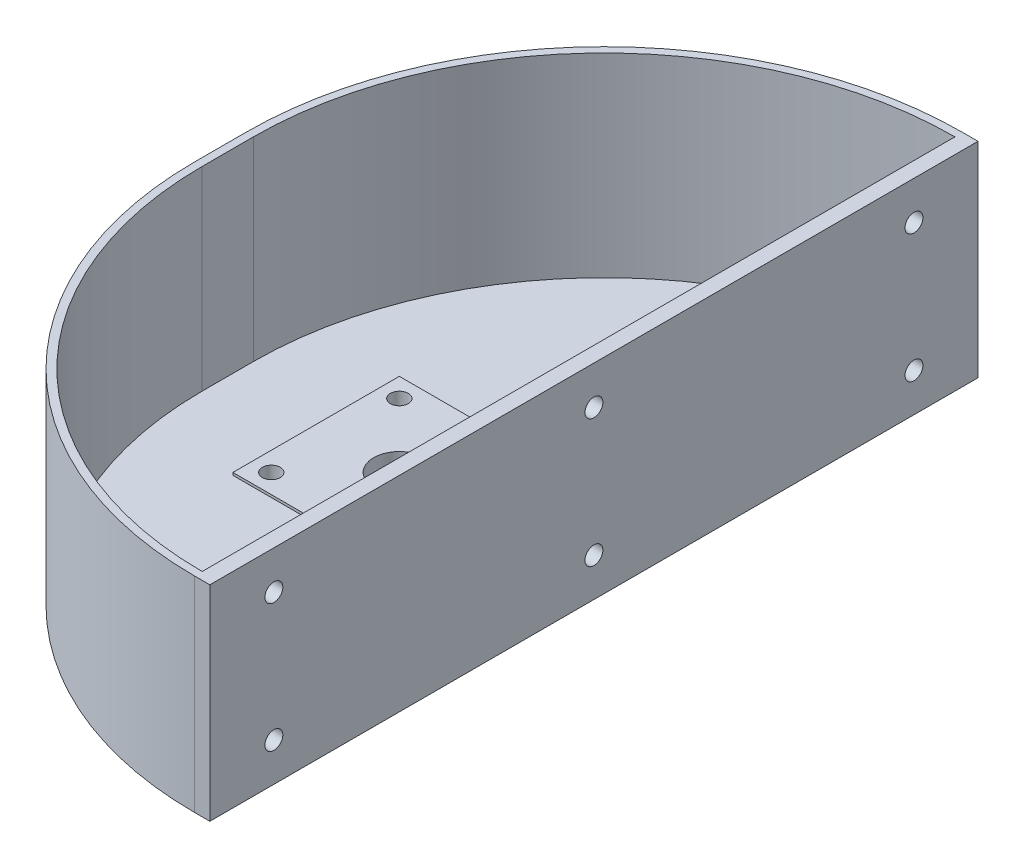
SolidWorks part; units mm, degrees
ref_plane "Спереди" through (0, 0, 0) normal (0, 0, 1) x (1, 0, 0)
ref_plane "Сверху" through (0, 0, 0) normal (0, 1, 0) x (1, 0, 0)
ref_plane "Справа" through (0, 0, 0) normal (1, 0, 0) x (0, 0, -1)
sketch "Эскиз1" plane through (0, 0, 0) normal (0, 1, 0) x (1, 0, 0)
  line L0 (0, 159.887) -> (0, 0) construction
  line L1 (0, 0) -> (281.7797, 0) construction
  line L3 (-70, -150) -> (70, -150)
  line L4 (-70, -150) -> (-70, 150)
  line L5 (-70, 150) -> (70, 150)
  line L6 (70, -150) -> (70, 150)
  line L7 (0, 150) -> (0, -150) construction
  line L8 (-70, 0) -> (70, 0) construction
  dimension "D1" = 300
  dimension "D2" = 140
extrude "Бобышка-Вытянуть1" add sketch "Эскиз1" along normal blind 4
sketch "Эскиз2" plane through (0, 0, 0) normal (0, 1, 0) x (1, 0, 0)
  line L1 (70, 150) -> (76, 150)
  line L2 (70, 150) -> (70, -150)
  line L3 (70, -150) -> (76, -150)
  line L4 (76, 150) -> (76, -150)
  dimension "D1" = 300
  dimension "D2" = 6
extrude "Бобышка-Вытянуть2" add sketch "Эскиз2" along normal blind 80
fillet "Скругление1" radius 140 2 edges at (-70, 2, -150) (-70, 2, 150)
sketch "Эскиз3" plane through (0, 4, 0) normal (0, 1, 0) x (1, 0, 0)
  line L1 (-32.5, -32.5) -> (32.5, -32.5)
  line L2 (-32.5, -32.5) -> (-32.5, 32.5)
  line L3 (-32.5, 32.5) -> (32.5, 32.5)
  line L4 (32.5, -32.5) -> (32.5, 32.5)
  line L5 (0, 32.5) -> (0, -32.5) construction
  line L6 (-32.5, 0) -> (32.5, 0) construction
  point P0 (0, 0)
  dimension "D1" = 65
extrude "Бобышка-Вытянуть3" add sketch "Эскиз3" along normal blind 1
sketch "Эскиз4" plane through (0, 5, 0) normal (0, 1, 0) x (1, 0, 0)
  line L1 (-25, -25) -> (25, -25) construction
  line L2 (-25, -25) -> (-25, 25) construction
  line L3 (-25, 25) -> (25, 25) construction
  line L4 (25, -25) -> (25, 25) construction
  line L5 (0, 25) -> (0, -25) construction
  line L6 (-25, 0) -> (25, 0) construction
  circle A0 centre (-25, 25) radius 3.5
  circle A1 centre (25, 25) radius 3.5
  circle A2 centre (-25, -25) radius 3.5
  circle A3 centre (25, -25) radius 3.5
  circle A4 centre (0, 0) radius 10
  point P0 (0, 0)
  dimension "D2" = 20
  dimension "D3" = 7
  dimension "D1" = 50
extrude "Вырез-Вытянуть1" cut sketch "Эскиз4" against normal through all
sketch "Эскиз9" plane through (0, 4, 0) normal (0, 1, 0) x (1, 0, 0)
  line L3 (-67, 10) -> (-67, -10)
  line L4 (-67, 10) -> (-67, -10)
  arc A6 (-67, -10) -> (70, -147) centre (70, -10) ccw
  arc A7 (70, 147) -> (-67, 10) centre (70, 10) ccw
  arc A8 (-67, -10) -> (70, -147) centre (70, -10) ccw
  arc A9 (70, 147) -> (-67, 10) centre (70, 10) ccw
  dimension "D1" = 3
extrude "Вытянуть-Тонкостенный1" add sketch "Эскиз9" along normal up to surface (76 mm away) thin
fillet "Скругление2" [suppressed] radius 140
sketch "Эскиз16" plane through (76, 0, 0) normal (1, 0, 0) x (0, 0, -1)
  line L0 (0, 111.0778) -> (0, 40) construction
  line L1 (0, 40) -> (205.7417, 40) construction
  line L2 (-150, 0) -> (150, 0) construction
  circle A0 centre (0, 65) radius 3.5
  circle A1 centre (0, 15) radius 3.5
  circle A2 centre (125, 65) radius 3.5
  circle A3 centre (-125, 65) radius 3.5
  circle A4 centre (-125, 15) radius 3.5
  circle A5 centre (125, 15) radius 3.5
  point P12 (105.815, 65)
  dimension "D2" = 7
  dimension "D3" = 25
  dimension "D4" = 125
  dimension "D1" = 40
extrude "Вырез-Вытянуть6" cut sketch "Эскиз16" against normal blind 20
